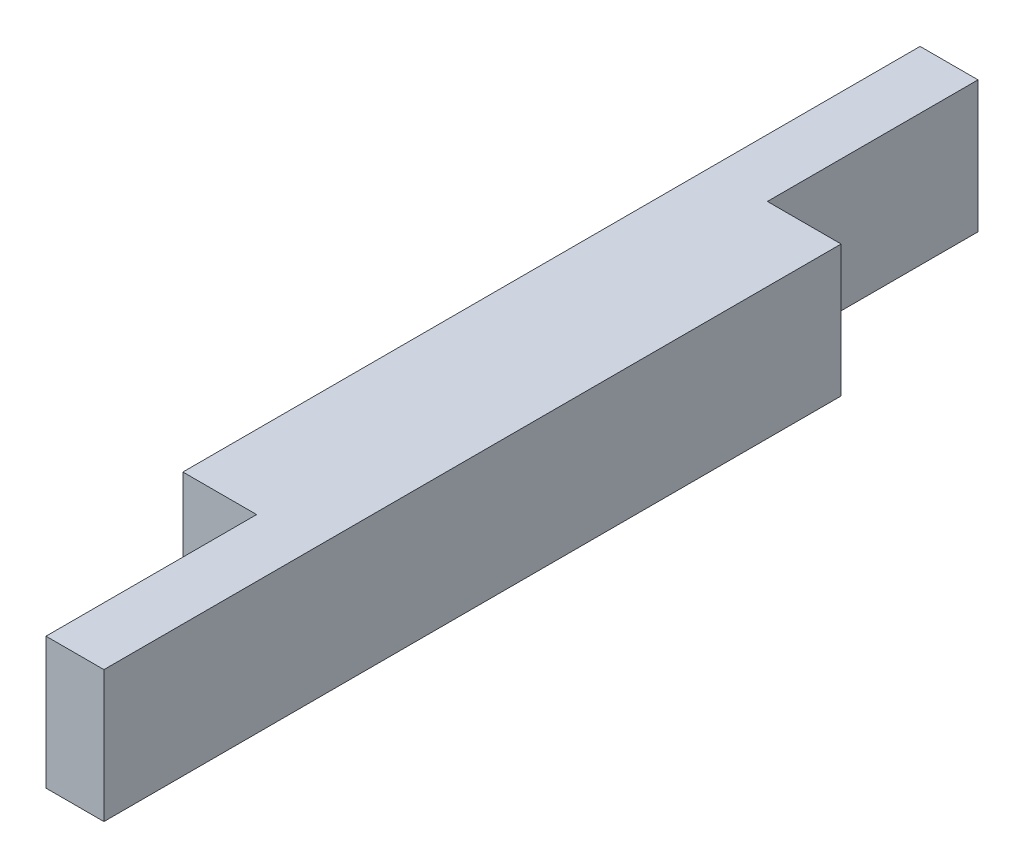
SolidWorks part; units mm, degrees
ref_plane "Front Plane" through (0, 0, 0) normal (0, 0, 1) x (1, 0, 0)
ref_plane "Top Plane" through (0, 0, 0) normal (0, 1, 0) x (1, 0, 0)
ref_plane "Right Plane" through (0, 0, 0) normal (1, 0, 0) x (0, 0, -1)
sketch "Sketch3" plane through (0, 0, 0) normal (0, 1, 0) x (1, 0, 0)
  line L1 (-12.5, 0) -> (12.5, 0)
  line L2 (-12.5, 0) -> (-12.5, 180)
  line L3 (-12.5, 180) -> (12.5, 180)
  line L4 (12.5, 0) -> (12.5, 180)
  point P4 (0, 0)
  point P5 (-14.1318, 0)
  point P7 (12.5, 0)
  dimension "D1" = 25
  dimension "D2" = 180
extrude "Boss-Extrude1" add sketch "Sketch3" along normal blind 25 contours L4 L3 L2 L1
sketch "Sketch4" plane through (0, 25, 0) normal (0, 1, 0) x (1, 0, 0)
  line L0 (-12.5, 0) -> (-12.5, 180) construction
  line L1 (1.5, 0) -> (-12.5, 0)
  line L2 (1.5, 0) -> (1.5, 40)
  line L3 (1.5, 40) -> (-12.5, 40)
  line L4 (-12.5, 0) -> (-12.5, 40)
  line L7 (12.5, 180) -> (-1.5, 180)
  line L8 (12.5, 180) -> (12.5, 140)
  line L9 (12.5, 140) -> (-1.5, 140)
  line L10 (-1.5, 180) -> (-1.5, 140)
  line M3 (12.5, 0) -> (12.5, 180)
  line M4 (12.5, 180) -> (-12.5, 180)
  dimension "D1" = 40
  dimension "D2" = 14
  dimension "D3" = 40
  dimension "D4" = 14
extrude "Cut-Extrude1" cut sketch "Sketch4" against normal through all contours L10 L9 M4 M3 | L3 L4 L1 L2
sketch "Sketch5" plane through (1.5, 0, 0) normal (-1, 0, 0) x (0, 0, 1)
  line L1 (0, 0) -> (0, 25) construction
  line L3 (0, 0) -> (-40, 0) construction
  point P0 (-25, 12.5)
  dimension "D1" = 25
  dimension "D2" = 12.5
